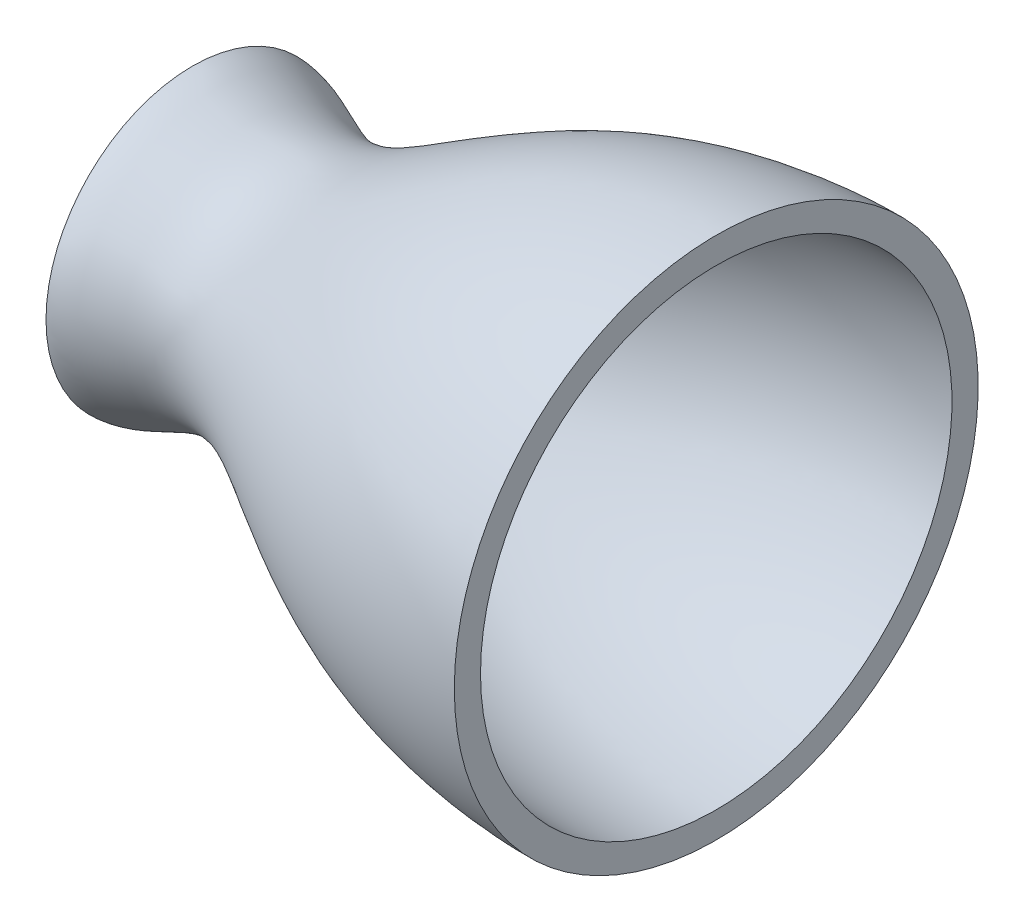
SolidWorks part; units mm, degrees
ref_plane "Front Plane" through (0, 0, 0) normal (0, 0, 1) x (1, 0, 0)
ref_plane "Top Plane" through (0, 0, 0) normal (0, 1, 0) x (1, 0, 0)
ref_plane "Right Plane" through (0, 0, 0) normal (1, 0, 0) x (0, 0, -1)
sketch "Sketch2" plane through (0, 0, 0) normal (0, 0, 1) x (1, 0, 0)
  line L0 (0, 0) -> (0, 60508.0966) construction
  line L1 (500, 1.505) -> (500, 60509.6017) construction
  line L4 (0, -139.7114) -> (500, -139.7114) construction
  line L7 (0, 0) -> (0, -25)
  line L8 (500, 110.2886) -> (500, 85.2417)
  spline S0 degree 3 poles (0, 0) (12.6644, 0) (40.3445, -12.4665) (102.9697, -37.5622) (196.5708, 19.7193) (321.2713, 89.3057) (435.2446, 110.2886) (500, 110.2886) knots 0 0 0 0 0.073976 0.164365 0.37118 0.629474 1 1 1 1
  spline S1 degree 3 poles (0, -25) (12.6644, -25) (40.3445, -37.4665) (102.9697, -62.5622) (196.5708, -5.2807) (321.2713, 64.3057) (435.2446, 85.2886) (500, 85.2886) knots 0 0 0 0 0.073976 0.164365 0.37118 0.629474 1 1 1 1
  dimension "D1" = 500
  dimension "D2" = 250
revolve "Revolve3" add sketch "Sketch2" angle 360 about L4
